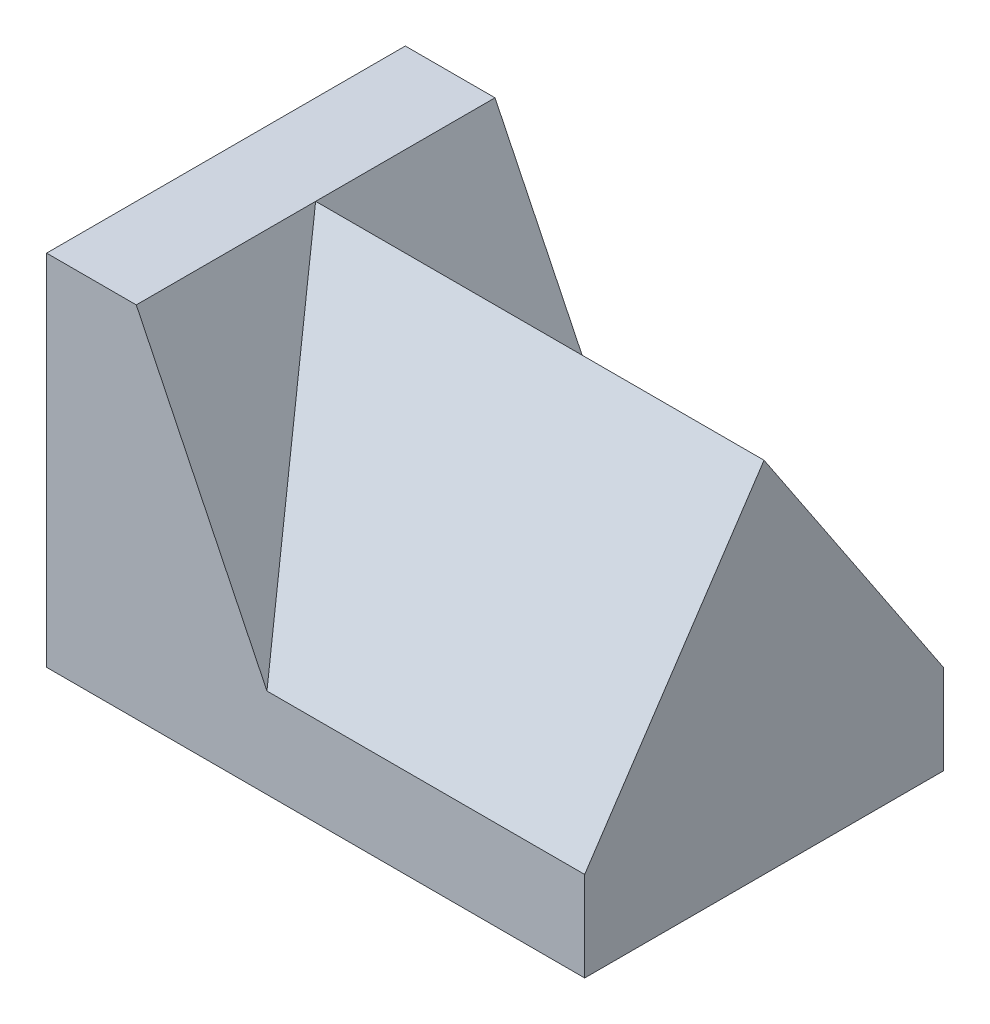
SolidWorks part; units mm, degrees
ref_plane "Front" through (0, 0, 0) normal (0, 0, 1) x (1, 0, 0)
ref_plane "Top" through (0, 0, 0) normal (0, 1, 0) x (1, 0, 0)
ref_plane "Right" through (0, 0, 0) normal (1, 0, 0) x (0, 0, -1)
sketch "草圖1" plane through (0, 0, 0) normal (0, 0, 1) x (1, 0, 0)
  line L0 (0, 0) -> (26.8125, 0) construction
  line L1 (0, 0) -> (0, 15.2188) construction
  line L3 (-15, 10) -> (15, 10)
  line L4 (-15, 10) -> (-15, -10)
  line L5 (-15, -10) -> (15, -10)
  line L6 (15, 10) -> (15, -10)
  line L7 (-15, 10) -> (15, -10) construction
  line L8 (-15, -10) -> (15, 10) construction
  point P1 (0, 0)
  dimension "D1" = 30
  dimension "D2" = 20
extrude "填料-伸長1" add sketch "草圖1" along normal blind 20
sketch "草圖10" plane through (0, 0, 0) normal (0, 0, -1) x (-1, 0, 0)
  line L0 (-15, -5) -> (2.7146, -5)
  line L1 (-15, -10) -> (-15, 10) construction
  line L2 (2.7146, -5) -> (10, 10)
  line L3 (-15, 10) -> (15, 10) construction
  line L4 (10, 10) -> (-15, 10)
  line L5 (-15, 10) -> (-15, -5)
  line L6 (15, -10) -> (-15, -10) construction
  line L7 (15, 10) -> (15, -10) construction
  dimension "D1" = 5
  dimension "D2" = 5
extrude "除料-伸長4" cut sketch "草圖10" against normal through all
sketch "草圖11" plane through (-15, 0, 0) normal (-1, 0, 0) x (0, 0, 1)
  line L0 (0, -5) -> (10, 10)
  line L1 (0, 10) -> (0, -10) construction
  line L2 (20, 10) -> (0, 10) construction
  line L3 (10, 10) -> (20, -5)
  line L4 (20, 10) -> (20, -10) construction
  line L5 (0, -5) -> (0, 10)
  line L6 (0, 10) -> (20, 10)
  line L7 (20, 10) -> (20, -5)
  line L9 (20, -10) -> (0, -10) construction
  line L10 (0, -5) -> (20, -5)
  dimension "D1" = 5
  dimension "D2" = 5
extrude "填料-伸長6" add sketch "草圖11" against normal blind 30 contours L0 L10 L3
